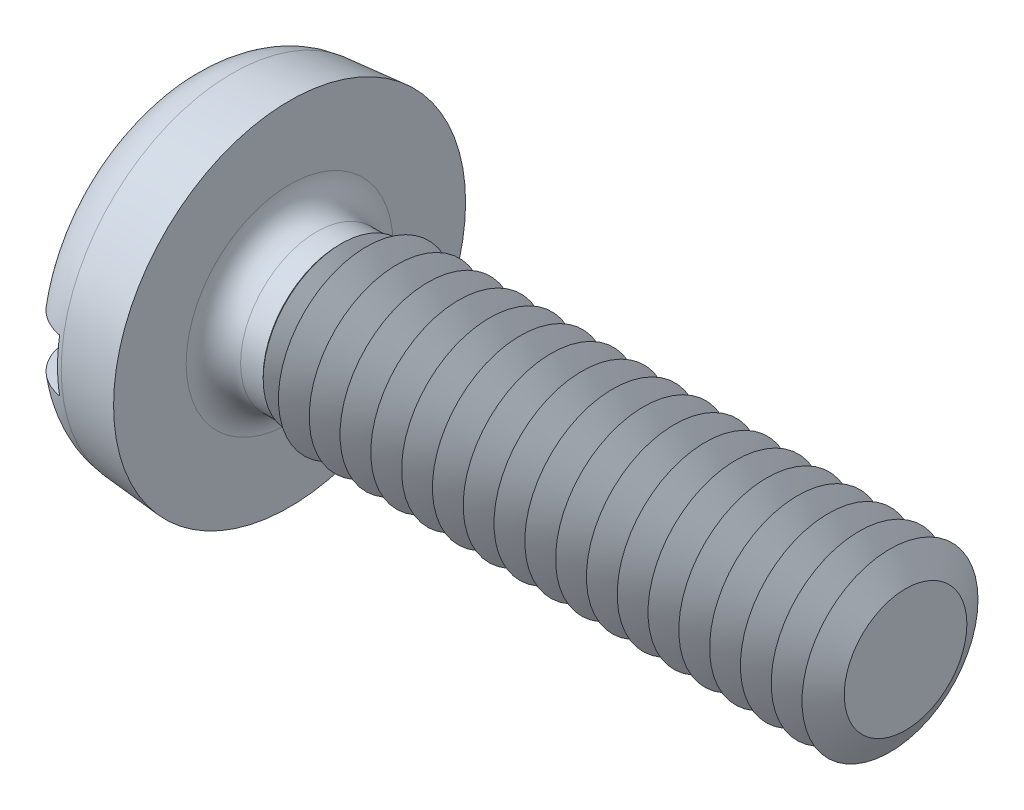
SolidWorks part; units mm, degrees
revolve "基体-旋转" add sketch "草图3" angle 360 about L0
sketch "草图3" plane through (0, 0, 0) normal (0, 0, 1) x (1, 0, 0)
  line L0 (-2.477, 0) -> (6.7868, 0) construction
  line L1 (0, 0) -> (16.4, 0)
  line L2 (16.4, 0) -> (16.4, 2)
  line L3 (16.4, 2) -> (3.8, 2)
  line L4 (2.4, 2.35) -> (2.4, 4)
  line L5 (3.8, 2) -> (3.532, 1.732)
  line L6 (3.532, 1.732) -> (3.018, 1.732)
  line L7 (2.4, 4) -> (1.0954, 3.8859)
  line L9 (0, 2.6904) -> (0, 0)
  arc A0 (3.018, 1.732) -> (2.4, 2.35) centre (3.018, 2.35) cw
  arc A1 (1.0954, 3.8859) -> (0, 2.6904) centre (1.2, 2.6904) ccw
  dimension "D5" = 1.2
  dimension "dk" = 8
  dimension "d" = 4
  dimension "D2" = 5
  dimension "l" = 14
  dimension "D1" = 45
  dimension "D3" = 3.464
  dimension "D4" = 12.6
  dimension "da" = 4.7
  dimension "k" = 2.4
cosmetic thread "装饰螺纹线1" parameters "D1"=12.6, "D2"=3.464
ref_plane "前视" through (0, 0, 0) normal (0, 0, 1) x (1, 0, 0)
ref_plane "上视" through (0, 0, 0) normal (0, 1, 0) x (1, 0, 0)
ref_plane "右视" through (0, 0, 0) normal (1, 0, 0) x (0, 0, -1)
sketch "尺寸草图" plane through (0, 0, 0) normal (0, 0, 1) x (1, 0, 0)
  line L0 (0, 0) -> (14, 0)
  line L1 (0, 0) -> (0, 8)
  line L2 (14, 0) -> (14, 4.7)
  point P5 (13.3, 0)
  point P6 (2.4, 0)
  point P7 (1.2, 0)
  point P8 (1.4, 0)
  point P9 (14, 0.2)
  point P10 (12.8, 0)
  point P11 (0, 1)
  point P12 (14, 4)
  dimension "dk" = 8
  dimension "d" = 4
  dimension "l" = 14
  dimension "da" = 4.7
  dimension "k" = 2.4
  dimension "P" = 0.7
  dimension "a" = 1.4
  dimension "n" = 1.2
  dimension "r" = 0.2
  dimension "rf" = 1.2
  dimension "t" = 1
sketch "草图4" plane through (0, 0, 0) normal (0, 0, 1) x (1, 0, 0)
  line L0 (0, 2.6904) -> (0, -2.6904) construction
  line L1 (0, 0.6) -> (1, 0.6)
  line L2 (0, 0.6) -> (0, -0.6)
  line L3 (0, -0.6) -> (1, -0.6)
  line L4 (1, 0.6) -> (1, -0.6)
  point P6 (0, 0)
  dimension "n" = 1.2
  dimension "t" = 1
extrude "切除-拉伸1" cut sketch "草图4" against normal mid plane 100
sketch "草图5" plane through (0, 0, 0) normal (0, 0, 1) x (1, 0, 0)
  line L0 (16.0462, 2) -> (16.7462, 2)
  line L1 (16.7462, 2) -> (16.4, 1.3938)
  line L2 (16.4, 1.3938) -> (16.0462, 2)
  line L3 (16.4, 2) -> (3.8, 2) construction
  line L4 (16.4, -2) -> (16.4, 2) construction
  line L5 (6.175, 0) -> (-0.2582, 0) construction
  line L6 (-2.477, 0) -> (6.7868, 0) construction
  dimension "P" = 0.7
  dimension "D1" = 0.6062
  dimension "D2" = 60
revolve "切除-旋转1" cut sketch "草图5" angle 360 about L5
pattern_linear "阵列(线性)1" count 19 spacing 0.7 along (-1, 0, 0) of "切除-旋转1"
equation "\"l@草图3\" = \"l@尺寸草图\""
equation "\"dk@草图3\"=\"dk@尺寸草图\""
equation "\"da@草图3\" = \"da@尺寸草图\""
equation "\"D3@草图3\" = \"d@尺寸草图\"*0.866"
equation "\"D4@草图3\" = \"l@尺寸草图\"-\"a@尺寸草图\""
equation "\"d@草图3\" = \"d@尺寸草图\""
equation "\"D2@装饰螺纹线1\" = \"d@尺寸草图\"*0.866"
equation "\"D1@装饰螺纹线1\" = \"l@尺寸草图\"-\"a@尺寸草图\""
equation "\"n@草图4\" = \"n@尺寸草图\""
equation "\"t@草图4\" = \"t@尺寸草图\""
equation "\"P@草图5\" = \"P@尺寸草图\""
equation "\"D1@草图5\" = \"P@草图5\"*0.866"
equation "\"D3@阵列(线性)1\" = \"P@尺寸草图\""
equation "\"D1@阵列(线性)1\" = (\"l@尺寸草图\"-\"a@尺寸草图\")/\"P@尺寸草图\"+1"
equation "\"k@草图3\"=\"k@尺寸草图\""
equation "\"D5@草图3\"=\"rf@尺寸草图\""
